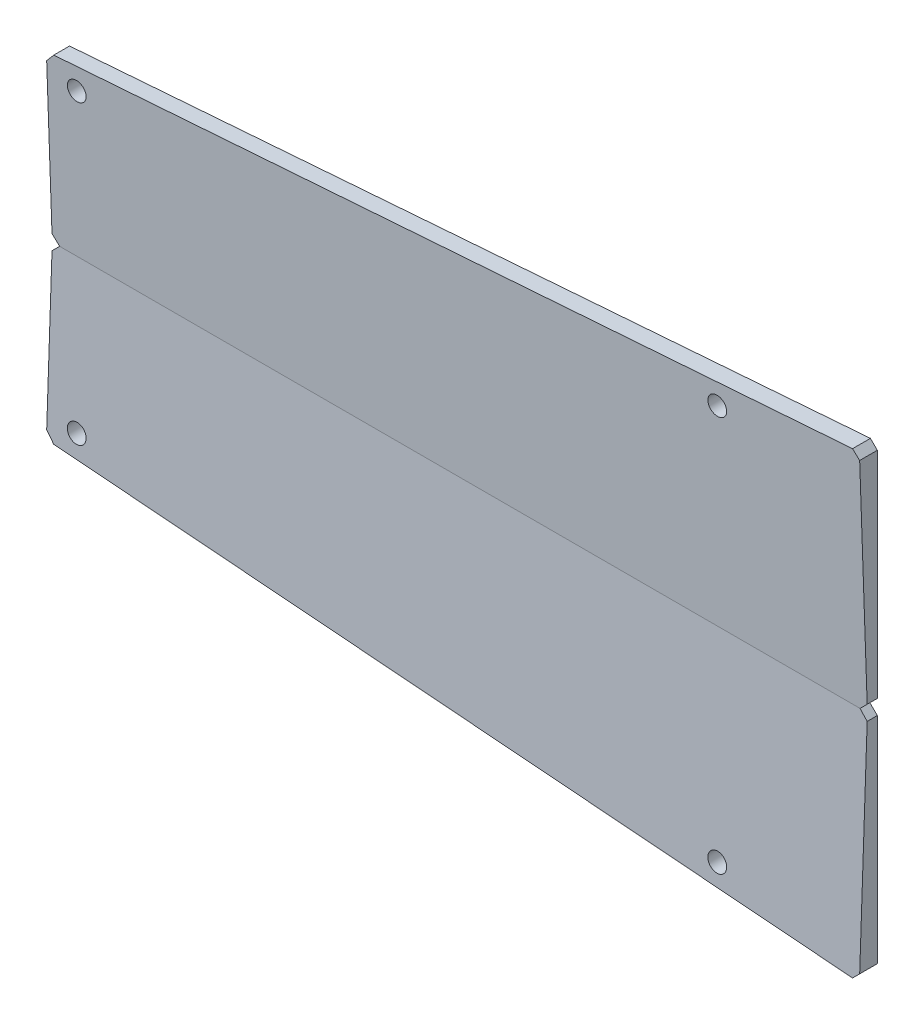
SolidWorks part; units mm, degrees
material "ABS PC"
ref_plane "Plan de face" through (0, 0, 0) normal (0, 0, 1) x (1, 0, 0)
ref_plane "Plan de dessus" through (0, 0, 0) normal (0, 1, 0) x (1, 0, 0)
ref_plane "Plan de droite" through (0, 0, 0) normal (1, 0, 0) x (0, 0, -1)
sketch "Esquisse1" plane through (0, 0, 0) normal (0, 0, 1) x (1, 0, 0)
  line L0 (-49.4389, 0) -> (115.5611, 0)
  line L1 (115.5611, 0) -> (115.5611, 46.5)
  line L2 (115.5611, 46.5) -> (-49.4389, 34)
  line L3 (-49.4389, 34) -> (-49.4389, 0)
  circle A0 centre (86.5611, 40) radius 1.9
  circle A1 centre (-43.4389, 30) radius 1.9
  dimension "D4" = 6
  dimension "D1" = 165
  dimension "D2" = 34
  dimension "D3" = 46.5
  dimension "D5" = 4
  dimension "D6" = 130
  dimension "D7" = 6.5
extrude "Extrusion1" add sketch "Esquisse1" along normal blind 2
draft "Dépouille1" type of draft neutral plane draft angle 2 faces to draft 1 face at (88.4611, 40, 2) neutral plane through (-49.4389, 0, 2) neutral plane normal (0, -1, 0) parameters "D1"=2
chamfer "Chanfrein1" distance 1.5 angle 45 1 edges at (115.5611, 46.5, 1.8119)
chamfer "Chanfrein2" distance 1.5 angle 45 1 edges at (115.5611, 0, 1)
chamfer "Chanfrein3" distance 1.5 angle 45 1 edges at (-49.4389, 0, 1)
chamfer "Chanfrein4" distance 1.5 angle 45 1 edges at (-49.4389, 34, 1.5937)
mirror "Symétrie1" about plane through (-49.4389, 0, 2) normal (0, 1, 0) of bodies 101
